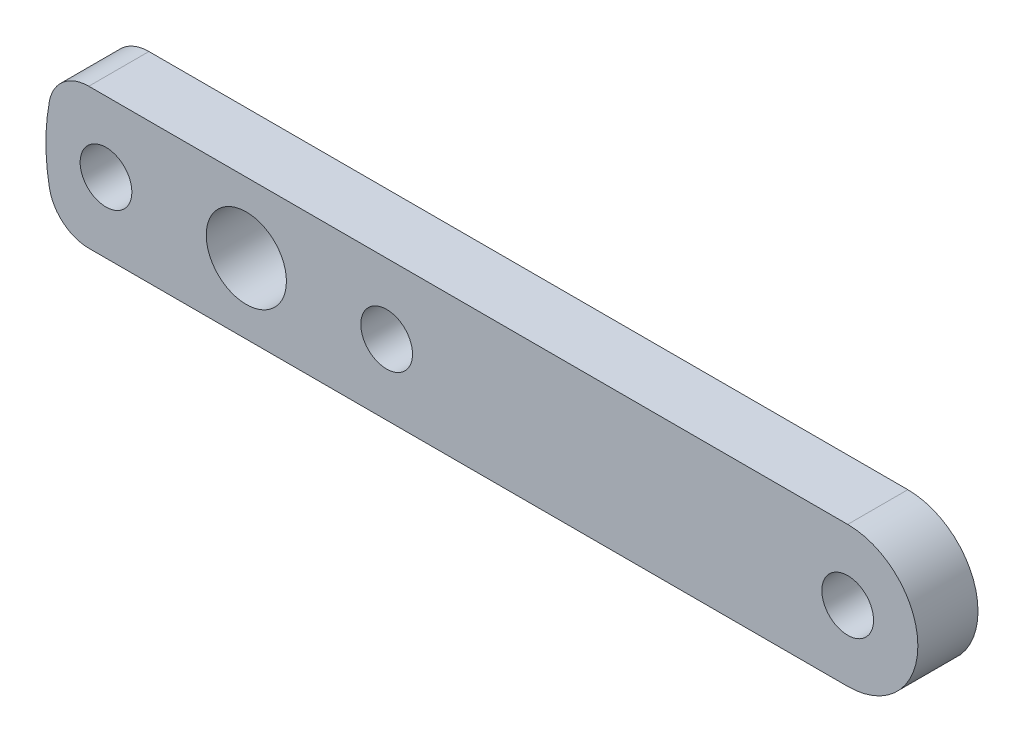
SolidWorks part; units mm, degrees
ref_plane "Front Plane" through (0, 0, 0) normal (0, 0, 1) x (1, 0, 0)
ref_plane "Top Plane" through (0, 0, 0) normal (0, 1, 0) x (1, 0, 0)
ref_plane "Right Plane" through (0, 0, 0) normal (1, 0, 0) x (0, 0, -1)
sketch "Sketch1" plane through (0, 0, 0) normal (0, 0, 1) x (1, 0, 0)
  line L0 (-9.3675, 3.5) -> (30, 3.5)
  line L1 (30, -3.5) -> (-9.3675, -3.5)
  line L2 (-7, 0) -> (7, 0) construction
  arc A0 (-9.3675, -3.5) -> (-9.3675, 3.5) centre (0, 0) cw
  arc A1 (30, 3.5) -> (30, -3.5) centre (30, 0) cw
  circle A2 centre (-7, 0) radius 1.29
  circle A3 centre (7, 0) radius 1.29
  circle A4 centre (30, 0) radius 1.29
  circle A5 centre (0, 0) radius 2
  point P6 (-10, 0)
  point P12 (0, 0)
  dimension "D1" = 10
  dimension "D2" = 7
  dimension "D4" = 2.58
  dimension "D6" = 4
  dimension "D3" = 30
  dimension "D5" = 14
extrude "Boss-Extrude1" add sketch "Sketch1" along normal mid plane 3
fillet "Fillet1" radius 2 2 edges at (-9.3675, -3.5, 0) (-9.3675, 3.5, 0)
